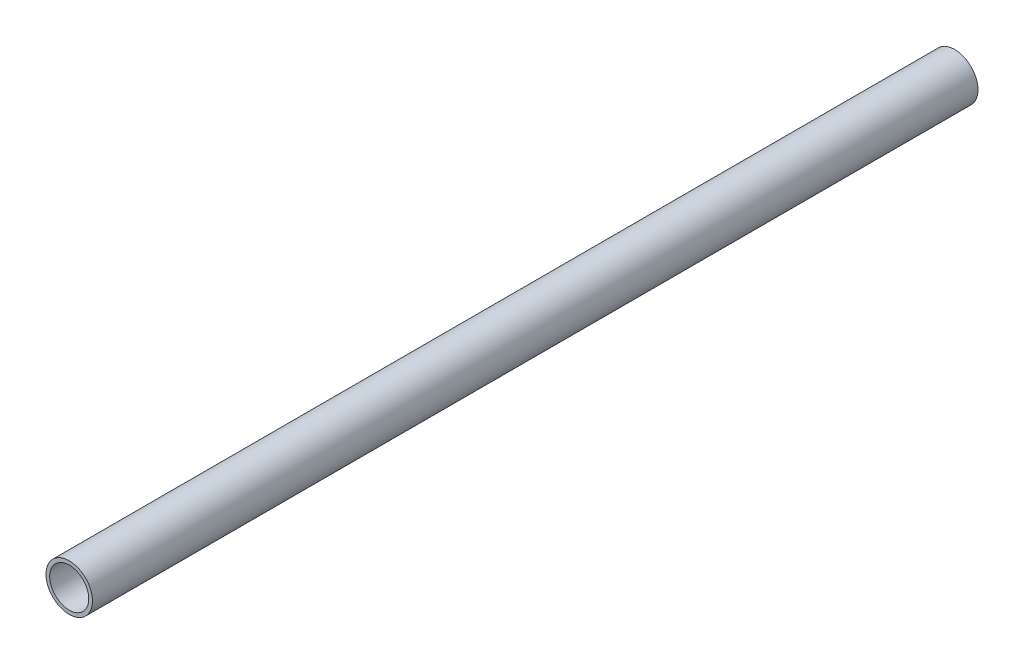
SolidWorks part; units mm, degrees
ref_plane "Alzado" through (0, 0, 0) normal (0, 0, 1) x (1, 0, 0)
ref_plane "Planta" through (0, 0, 0) normal (0, 1, 0) x (1, 0, 0)
ref_plane "Vista lateral" through (0, 0, 0) normal (1, 0, 0) x (0, 0, -1)
sketch "Croquis1" plane through (0, 0, 0) normal (0, 0, 1) x (1, 0, 0)
  circle A0 centre (0, 0) radius 12.5
  circle A1 centre (0, 0) radius 10.5
  dimension "D1" = 25
  dimension "D2" = 2
extrude "Saliente-Extruir1" add sketch "Croquis1" along normal blind 476
